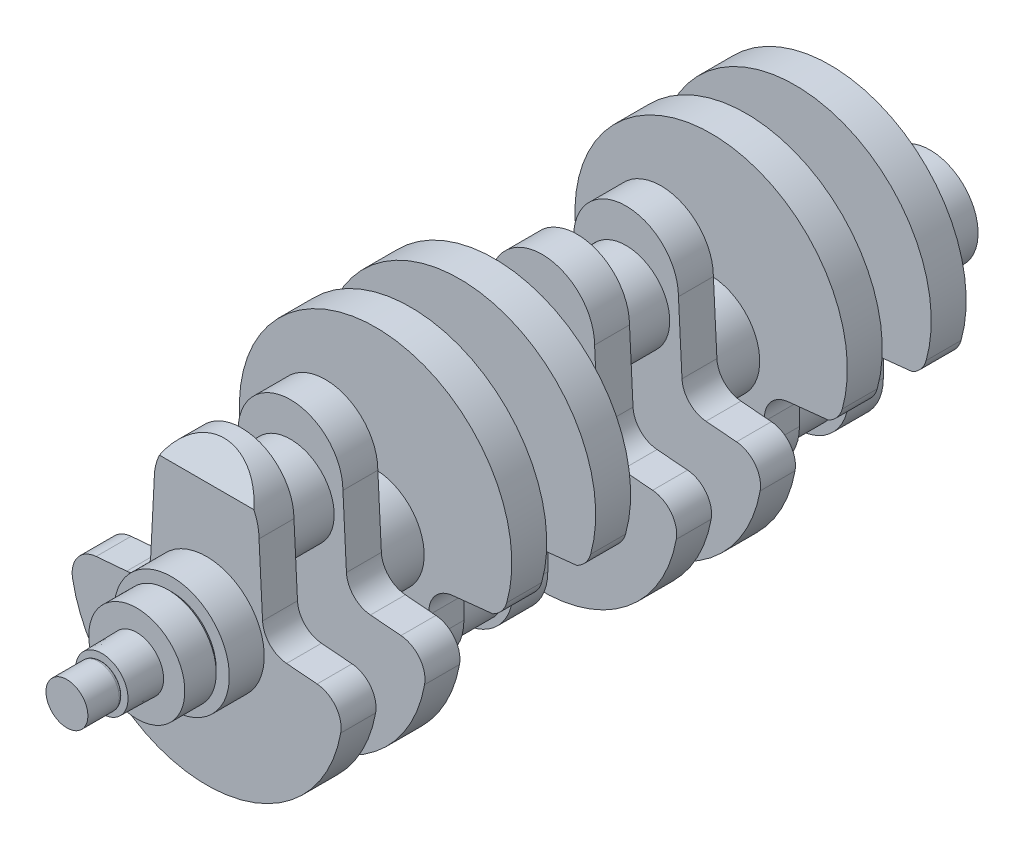
SolidWorks part; units mm, degrees
ref_plane "Front Plane" through (0, 0, 0) normal (0, 0, 1) x (1, 0, 0)
ref_plane "Top Plane" through (0, 0, 0) normal (0, 1, 0) x (1, 0, 0)
ref_plane "Right Plane" through (0, 0, 0) normal (1, 0, 0) x (0, 0, -1)
sketch "Sketch1" plane through (0, 0, 0) normal (0, 0, 1) x (1, 0, 0)
  circle A0 centre (0, 0) radius 12
  dimension "D1" = 24
extrude "Boss-Extrude1" add sketch "Sketch1" against normal blind 20
fillet "Fillet1" radius 2 1 edges at (12, 0, -20)
sketch "Sketch2" plane through (0, 0, -20) normal (0, 0, -1) x (-1, 0, 0)
  circle A0 centre (0, 0) radius 15
  dimension "D1" = 30
extrude "Boss-Extrude2" add sketch "Sketch2" along normal blind 20 draft 1 draft outward yes
sketch "Sketch3" plane through (0, 0, -40) normal (0, 0, -1) x (-1, 0, 0)
  circle A0 centre (0, 0) radius 27.5
  dimension "D1" = 55
extrude "Boss-Extrude3" add sketch "Sketch3" along normal blind 20
chamfer "Chamfer1" distance 2 angle 45 1 edges at (-27.5, 0, -60)
sketch "Sketch4" plane through (0, 0, -60) normal (0, 0, -1) x (-1, 0, 0)
  circle A0 centre (0, 0) radius 33
  dimension "D1" = 66
extrude "Boss-Extrude4" add sketch "Sketch4" along normal blind 20 contours A0
sketch "Sketch5" plane through (0, 0, -80) normal (0, 0, -1) x (-1, 0, 0)
  line L0 (-35.7468, 0) -> (36.7846, 0) construction
  line L1 (0, 38.3413) -> (0, -38.3413) construction
  line L2 (-30, 56.7758) -> (-32.0194, 17.0656)
  line L3 (30, 56.7758) -> (32.0194, 17.0656)
  line L4 (-45.7552, 2.8791) -> (-63.2448, 1.4227)
  line L5 (45.7552, 2.8791) -> (63.2448, 1.4227)
  arc A0 (-30, 56.7758) -> (30, 56.7758) centre (0, 56.7758) cw
  arc A1 (-32.0194, 17.0656) -> (-45.7552, 2.8791) centre (-47, 17.8274) cw
  arc A2 (-63.2448, 1.4227) -> (-76.7619, -16.1875) centre (-62, -13.5255) ccw
  arc A3 (63.2448, 1.4227) -> (76.7619, -16.1875) centre (62, -13.5255) cw
  arc A4 (32.0194, 17.0656) -> (45.7552, 2.8791) centre (47, 17.8274) ccw
  arc A5 (-76.7619, -16.1875) -> (76.7619, -16.1875) centre (0, -2.3452) ccw
  dimension "D1" = 30
  dimension "D2" = 15
  dimension "D4" = 15
  dimension "D6" = 78
  dimension "D3" = 47
  dimension "D5" = 62
extrude "Boss-Extrude5" add sketch "Sketch5" along normal blind 20 contours A5 A3 L5 A4 L3 A0 L2 A1 L4 A2
sketch "Sketch6" plane through (0, 0, 0) normal (1, 0, 0) x (0, 0, -1)
  line L0 (90, 86.7758) -> (80, 69.7758)
  line L1 (80, 86.7758) -> (80, 56.7758) construction
  line L2 (100, 86.7758) -> (80, 86.7758) construction
  line L3 (80, 69.7758) -> (80, 86.7758)
  line L4 (80, 86.7758) -> (90, 86.7758)
  dimension "D1" = 17
extrude "Cut-Extrude2" cut sketch "Sketch6" against normal blind 46 and the other way blind 81 contours L0 L3 L4
sketch "Sketch7" plane through (0, 0, -100) normal (0, 0, -1) x (-1, 0, 0)
  line L0 (0, 79.2777) -> (0, -90.0743) construction
  line L1 (-80.2962, 0) -> (95.4795, 0) construction
  circle A1 centre (0, 42.18) radius 25
  point P9 (0, 0)
  point P10 (0, 0)
  point P11 (0, 0)
  dimension "D1" = 50
  dimension "D2" = 42.18
extrude "Boss-Extrude6" add sketch "Sketch7" along normal blind 28.03 contours A1
sketch "Sketch8" plane through (0, 0, -128.03) normal (0, 0, -1) x (-1, 0, 0)
  line L0 (-30, 56.7758) -> (-32.0194, 17.0656) construction
  line L1 (-45.7552, 2.8791) -> (-63.2448, 1.4227) construction
  line L2 (45.7552, 2.8791) -> (63.2448, 1.4227) construction
  line L3 (30, 56.7758) -> (32.0194, 17.0656) construction
  line L4 (-30, 56.7758) -> (-32.0194, 17.0656)
  line L5 (-45.7552, 2.8791) -> (-63.2448, 1.4227)
  line L6 (45.7552, 2.8791) -> (63.2448, 1.4227)
  line L7 (30, 56.7758) -> (32.0194, 17.0656)
  arc A0 (-45.7552, 2.8791) -> (-32.0194, 17.0656) centre (-47, 17.8274) ccw construction
  arc A3 (-63.2448, 1.4227) -> (-76.7619, -16.1875) centre (-62, -13.5255) ccw construction
  arc A4 (-76.7619, -16.1875) -> (76.7619, -16.1875) centre (0, -2.3452) ccw construction
  arc A5 (76.7619, -16.1875) -> (63.2448, 1.4227) centre (62, -13.5255) ccw construction
  arc A6 (32.0194, 17.0656) -> (45.7552, 2.8791) centre (47, 17.8274) ccw construction
  arc A7 (30, 56.7758) -> (-30, 56.7758) centre (0, 56.7758) ccw construction
  arc A8 (-45.7552, 2.8791) -> (-32.0194, 17.0656) centre (-47, 17.8274) ccw
  arc A9 (-63.2448, 1.4227) -> (-76.7619, -16.1875) centre (-62, -13.5255) ccw
  arc A10 (-76.7619, -16.1875) -> (76.7619, -16.1875) centre (0, -2.3452) ccw
  arc A11 (76.7619, -16.1875) -> (63.2448, 1.4227) centre (62, -13.5255) ccw
  arc A12 (32.0194, 17.0656) -> (45.7552, 2.8791) centre (47, 17.8274) ccw
  arc A13 (30, 56.7758) -> (-30, 56.7758) centre (0, 56.7758) ccw
extrude "Boss-Extrude7" add sketch "Sketch8" along normal blind 20 separate body
sketch "Sketch9" plane through (0, 0, -148.03) normal (0, 0, -1) x (-1, 0, 0)
  circle A0 centre (0, 0) radius 28.5
  dimension "D1" = 57
extrude "Boss-Extrude8" add sketch "Sketch9" along normal blind 28.03
sketch "Sketch11" plane through (0, 0, -176.06) normal (0, 0, -1) x (-1, 0, 0)
  line L0 (-31.2458, -28.3954) -> (-31.2458, -40.9949)
  line L1 (-81.7562, 0) -> (80.2962, 0) construction
  line L2 (0, 95.629) -> (-1.7519, -96.498) construction
  line L3 (-67.8054, -9.5229) -> (-44.5982, -11.9675)
  line L4 (65.8767, -10.7419) -> (42.6287, -12.7629)
  line L5 (28.979, -28.9446) -> (28.7492, -41.5419)
  arc A0 (-44.5982, -11.9675) -> (-31.2458, -28.3954) centre (-46.1696, -26.8849) cw
  arc A1 (65.8767, -10.7419) -> (74.0176, -1.4124) centre (59.6527, 2.9059) ccw
  arc A2 (-67.8054, -9.5229) -> (-75.7749, -0.0465) centre (-61.3336, 4.0091) cw
  arc A3 (-75.7749, -0.0465) -> (74.0176, -1.4124) centre (-0.6801, 21.043) cw
  arc A4 (-31.2458, -40.9949) -> (28.7492, -41.5419) centre (-1.2458, -40.9949) ccw
  arc A5 (42.6287, -12.7629) -> (28.979, -28.9446) centre (43.9278, -27.7065) ccw
  point P4 (30.366, -41.0096)
  point P23 (0, 0)
  dimension "D1" = 15
  dimension "D2" = 15
  dimension "D3" = 78
  dimension "D4" = 30
extrude "Boss-Extrude9" add sketch "Sketch11" along normal blind 20
sketch "Sketch12" plane through (0, 0, -196.06) normal (0, 0, -1) x (-1, 0, 0)
  circle A0 centre (-1.9338, -42) radius 25
  dimension "D1" = 50
  dimension "D2" = 42
extrude "Boss-Extrude10" add sketch "Sketch12" along normal blind 28.03
sketch "Sketch13" plane through (0, 0, -224.09) normal (0, 0, -1) x (-1, 0, 0)
  line L4 (-31.2458, -28.3954) -> (-31.2458, -40.9949)
  line L5 (28.7492, -41.5419) -> (28.979, -28.9446)
  line L6 (42.6287, -12.7629) -> (65.8767, -10.7419)
  line L7 (-67.8054, -9.5229) -> (-44.5982, -11.9675)
  line L8 (-31.2458, -28.3954) -> (-31.2458, -40.9949)
  line L9 (28.7492, -41.5419) -> (28.979, -28.9446)
  line L10 (42.6287, -12.7629) -> (65.8767, -10.7419)
  line L11 (-67.8054, -9.5229) -> (-44.5982, -11.9675)
  arc A6 (-31.2458, -28.3954) -> (-44.5982, -11.9675) centre (-46.1696, -26.8849) ccw
  arc A7 (-31.2458, -40.9949) -> (28.7492, -41.5419) centre (-1.2458, -40.9949) ccw
  arc A8 (42.6287, -12.7629) -> (28.979, -28.9446) centre (43.9278, -27.7065) ccw
  arc A9 (65.8767, -10.7419) -> (74.0176, -1.4124) centre (59.6527, 2.9059) ccw
  arc A10 (74.0176, -1.4124) -> (-75.7749, -0.0465) centre (-0.6801, 21.043) ccw
  arc A11 (-75.7749, -0.0465) -> (-67.8054, -9.5229) centre (-61.3336, 4.0091) ccw
  arc A12 (-31.2458, -28.3954) -> (-44.5982, -11.9675) centre (-46.1696, -26.8849) ccw
  arc A13 (-31.2458, -40.9949) -> (28.7492, -41.5419) centre (-1.2458, -40.9949) ccw
  arc A14 (42.6287, -12.7629) -> (28.979, -28.9446) centre (43.9278, -27.7065) ccw
  arc A15 (65.8767, -10.7419) -> (74.0176, -1.4124) centre (59.6527, 2.9059) ccw
  arc A16 (74.0176, -1.4124) -> (-75.7749, -0.0465) centre (-0.6801, 21.043) ccw
  arc A17 (-75.7749, -0.0465) -> (-67.8054, -9.5229) centre (-61.3336, 4.0091) ccw
  dimension "D1" = 0
extrude "Boss-Extrude11" add sketch "Sketch13" along normal blind 20
sketch "Sketch14" plane through (0, 0, -244.09) normal (0, 0, -1) x (-1, 0, 0)
  circle A0 centre (0, 0) radius 28.5
  dimension "D1" = 57
extrude "Boss-Extrude12" add sketch "Sketch14" along normal blind 28.03
sketch "Sketch15" plane through (0, 0, -272.12) normal (0, 0, -1) x (-1, 0, 0)
  line L4 (63.2448, 1.4227) -> (45.7552, 2.8791)
  line L5 (32.0194, 17.0656) -> (30, 56.7758)
  line L6 (-30, 56.7758) -> (-32.0194, 17.0656)
  line L7 (-45.7552, 2.8791) -> (-63.2448, 1.4227)
  line L8 (63.2448, 1.4227) -> (45.7552, 2.8791)
  line L9 (32.0194, 17.0656) -> (30, 56.7758)
  line L10 (-30, 56.7758) -> (-32.0194, 17.0656)
  line L11 (-45.7552, 2.8791) -> (-63.2448, 1.4227)
  arc A6 (-63.2448, 1.4227) -> (-76.7619, -16.1875) centre (-62, -13.5255) ccw
  arc A7 (-76.7619, -16.1875) -> (76.7619, -16.1875) centre (0, -2.3452) ccw
  arc A8 (76.7619, -16.1875) -> (63.2448, 1.4227) centre (62, -13.5255) ccw
  arc A9 (32.0194, 17.0656) -> (45.7552, 2.8791) centre (47, 17.8274) ccw
  arc A10 (30, 56.7758) -> (-30, 56.7758) centre (0, 56.7758) ccw
  arc A11 (-45.7552, 2.8791) -> (-32.0194, 17.0656) centre (-47, 17.8274) ccw
  arc A12 (-63.2448, 1.4227) -> (-76.7619, -16.1875) centre (-62, -13.5255) ccw
  arc A13 (-76.7619, -16.1875) -> (76.7619, -16.1875) centre (0, -2.3452) ccw
  arc A14 (76.7619, -16.1875) -> (63.2448, 1.4227) centre (62, -13.5255) ccw
  arc A15 (32.0194, 17.0656) -> (45.7552, 2.8791) centre (47, 17.8274) ccw
  arc A16 (30, 56.7758) -> (-30, 56.7758) centre (0, 56.7758) ccw
  arc A17 (-45.7552, 2.8791) -> (-32.0194, 17.0656) centre (-47, 17.8274) ccw
  dimension "D1" = 0
extrude "Boss-Extrude13" add sketch "Sketch15" along normal blind 20
sketch "Sketch16" plane through (0, 0, -292.12) normal (0, 0, -1) x (-1, 0, 0)
  line L0 (0, 0) -> (0, 114.501) construction
  circle A0 centre (0, 42.18) radius 25
  point P5 (0, 0)
  point P6 (0, 0)
  dimension "D1" = 50
  dimension "D2" = 42.18
extrude "Boss-Extrude14" add sketch "Sketch16" along normal blind 28.03
sketch "Sketch17" plane through (0, 0, -320.15) normal (0, 0, -1) x (-1, 0, 0)
  line L4 (63.2448, 1.4227) -> (45.7552, 2.8791)
  line L5 (32.0194, 17.0656) -> (30, 56.7758)
  line L6 (-30, 56.7758) -> (-32.0194, 17.0656)
  line L7 (-45.7552, 2.8791) -> (-63.2448, 1.4227)
  line L8 (63.2448, 1.4227) -> (45.7552, 2.8791)
  line L9 (32.0194, 17.0656) -> (30, 56.7758)
  line L10 (-30, 56.7758) -> (-32.0194, 17.0656)
  line L11 (-45.7552, 2.8791) -> (-63.2448, 1.4227)
  arc A6 (-63.2448, 1.4227) -> (-76.7619, -16.1875) centre (-62, -13.5255) ccw
  arc A7 (-76.7619, -16.1875) -> (76.7619, -16.1875) centre (0, -2.3452) ccw
  arc A8 (76.7619, -16.1875) -> (63.2448, 1.4227) centre (62, -13.5255) ccw
  arc A9 (32.0194, 17.0656) -> (45.7552, 2.8791) centre (47, 17.8274) ccw
  arc A10 (30, 56.7758) -> (-30, 56.7758) centre (0, 56.7758) ccw
  arc A11 (-45.7552, 2.8791) -> (-32.0194, 17.0656) centre (-47, 17.8274) ccw
  arc A12 (-63.2448, 1.4227) -> (-76.7619, -16.1875) centre (-62, -13.5255) ccw
  arc A13 (-76.7619, -16.1875) -> (76.7619, -16.1875) centre (0, -2.3452) ccw
  arc A14 (76.7619, -16.1875) -> (63.2448, 1.4227) centre (62, -13.5255) ccw
  arc A15 (32.0194, 17.0656) -> (45.7552, 2.8791) centre (47, 17.8274) ccw
  arc A16 (30, 56.7758) -> (-30, 56.7758) centre (0, 56.7758) ccw
  arc A17 (-45.7552, 2.8791) -> (-32.0194, 17.0656) centre (-47, 17.8274) ccw
  dimension "D1" = 0
extrude "Boss-Extrude15" add sketch "Sketch17" along normal blind 20
sketch "Sketch18" plane through (0, 0, -340.15) normal (0, 0, -1) x (-1, 0, 0)
  circle A0 centre (0, 0) radius 28.5
  dimension "D1" = 57
extrude "Boss-Extrude16" add sketch "Sketch18" along normal blind 28.03
sketch "Sketch19" plane through (0, 0, -368.18) normal (0, 0, -1) x (-1, 0, 0)
  line L4 (-31.2458, -28.3954) -> (-31.2458, -40.9949)
  line L5 (28.7492, -41.5419) -> (28.979, -28.9446)
  line L6 (42.6287, -12.7629) -> (65.8767, -10.7419)
  line L7 (-67.8054, -9.5229) -> (-44.5982, -11.9675)
  line L8 (-31.2458, -28.3954) -> (-31.2458, -40.9949)
  line L9 (28.7492, -41.5419) -> (28.979, -28.9446)
  line L10 (42.6287, -12.7629) -> (65.8767, -10.7419)
  line L11 (-67.8054, -9.5229) -> (-44.5982, -11.9675)
  arc A6 (-31.2458, -28.3954) -> (-44.5982, -11.9675) centre (-46.1696, -26.8849) ccw
  arc A7 (-31.2458, -40.9949) -> (28.7492, -41.5419) centre (-1.2458, -40.9949) ccw
  arc A8 (42.6287, -12.7629) -> (28.979, -28.9446) centre (43.9278, -27.7065) ccw
  arc A9 (65.8767, -10.7419) -> (74.0176, -1.4124) centre (59.6527, 2.9059) ccw
  arc A10 (74.0176, -1.4124) -> (-75.7749, -0.0465) centre (-0.6801, 21.043) ccw
  arc A11 (-75.7749, -0.0465) -> (-67.8054, -9.5229) centre (-61.3336, 4.0091) ccw
  arc A12 (-31.2458, -28.3954) -> (-44.5982, -11.9675) centre (-46.1696, -26.8849) ccw
  arc A13 (-31.2458, -40.9949) -> (28.7492, -41.5419) centre (-1.2458, -40.9949) ccw
  arc A14 (42.6287, -12.7629) -> (28.979, -28.9446) centre (43.9278, -27.7065) ccw
  arc A15 (65.8767, -10.7419) -> (74.0176, -1.4124) centre (59.6527, 2.9059) ccw
  arc A16 (74.0176, -1.4124) -> (-75.7749, -0.0465) centre (-0.6801, 21.043) ccw
  arc A17 (-75.7749, -0.0465) -> (-67.8054, -9.5229) centre (-61.3336, 4.0091) ccw
  dimension "D1" = 0
extrude "Boss-Extrude17" add sketch "Sketch19" along normal blind 20
sketch "Sketch20" plane through (0, 0, -388.18) normal (0, 0, -1) x (-1, 0, 0)
  line L0 (0, 0) -> (0, -113.668) construction
  circle A0 centre (0, -42) radius 25
  point P5 (0, 0)
  point P6 (0, 0)
  dimension "D1" = 50
  dimension "D2" = 42
extrude "Boss-Extrude18" add sketch "Sketch20" along normal blind 28.03
sketch "Sketch21" plane through (0, 0, -416.21) normal (0, 0, -1) x (-1, 0, 0)
  line L4 (-31.2458, -28.3954) -> (-31.2458, -40.9949)
  line L5 (28.7492, -41.5419) -> (28.979, -28.9446)
  line L6 (42.6287, -12.7629) -> (65.8767, -10.7419)
  line L7 (-67.8054, -9.5229) -> (-44.5982, -11.9675)
  line L8 (-31.2458, -28.3954) -> (-31.2458, -40.9949)
  line L9 (28.7492, -41.5419) -> (28.979, -28.9446)
  line L10 (42.6287, -12.7629) -> (65.8767, -10.7419)
  line L11 (-67.8054, -9.5229) -> (-44.5982, -11.9675)
  arc A6 (-31.2458, -28.3954) -> (-44.5982, -11.9675) centre (-46.1696, -26.8849) ccw
  arc A7 (-31.2458, -40.9949) -> (28.7492, -41.5419) centre (-1.2458, -40.9949) ccw
  arc A8 (42.6287, -12.7629) -> (28.979, -28.9446) centre (43.9278, -27.7065) ccw
  arc A9 (65.8767, -10.7419) -> (74.0176, -1.4124) centre (59.6527, 2.9059) ccw
  arc A10 (74.0176, -1.4124) -> (-75.7749, -0.0465) centre (-0.6801, 21.043) ccw
  arc A11 (-75.7749, -0.0465) -> (-67.8054, -9.5229) centre (-61.3336, 4.0091) ccw
  arc A12 (-31.2458, -28.3954) -> (-44.5982, -11.9675) centre (-46.1696, -26.8849) ccw
  arc A13 (-31.2458, -40.9949) -> (28.7492, -41.5419) centre (-1.2458, -40.9949) ccw
  arc A14 (42.6287, -12.7629) -> (28.979, -28.9446) centre (43.9278, -27.7065) ccw
  arc A15 (65.8767, -10.7419) -> (74.0176, -1.4124) centre (59.6527, 2.9059) ccw
  arc A16 (74.0176, -1.4124) -> (-75.7749, -0.0465) centre (-0.6801, 21.043) ccw
  arc A17 (-75.7749, -0.0465) -> (-67.8054, -9.5229) centre (-61.3336, 4.0091) ccw
  dimension "D1" = 0
extrude "Boss-Extrude19" add sketch "Sketch21" along normal blind 20
sketch "Sketch22" plane through (0, 0, -436.21) normal (0, 0, -1) x (-1, 0, 0)
  circle A0 centre (0, 0) radius 33 construction
  circle A1 centre (0, 0) radius 33
extrude "Boss-Extrude20" add sketch "Sketch22" along normal blind 28
sketch "Sketch23" plane through (0, 0, -464.21) normal (0, 0, -1) x (-1, 0, 0)
  circle A0 centre (0, 0) radius 27.5 construction
  circle A1 centre (0, 0) radius 27.5
extrude "Boss-Extrude21" add sketch "Sketch23" along normal blind 30
